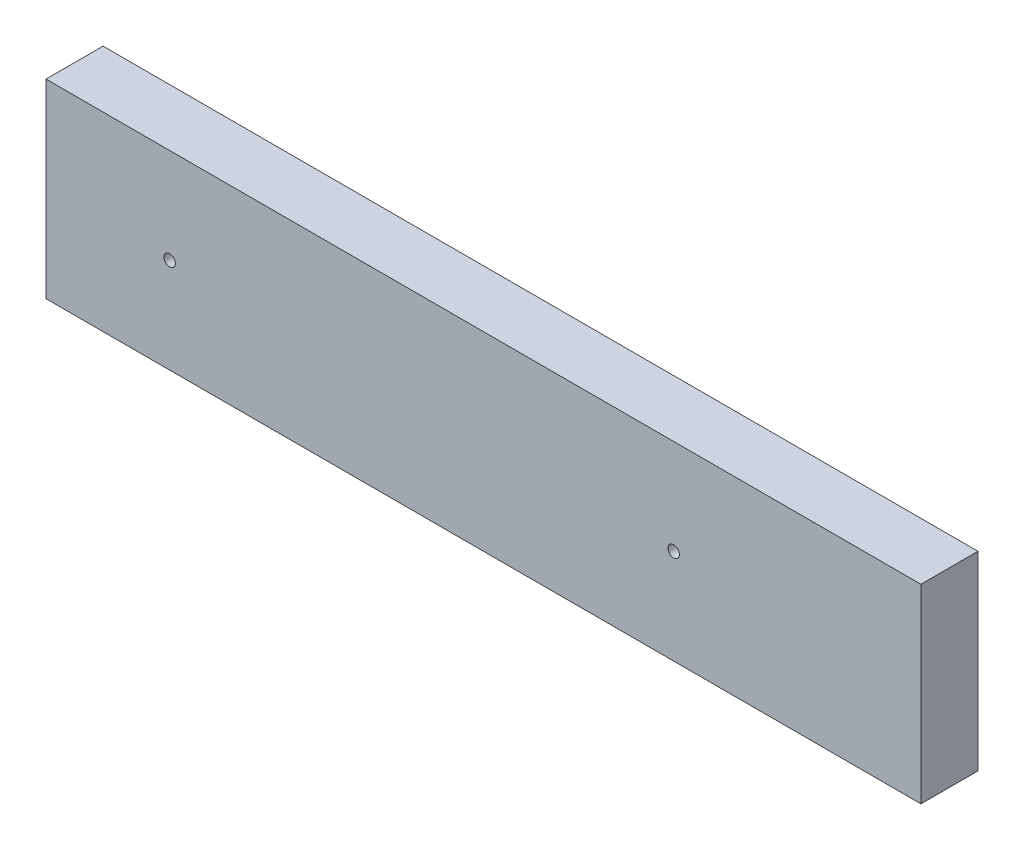
SolidWorks part; units mm, degrees
material "Pine"
ref_plane "Front Plane" through (0, 0, 0) normal (0, 0, 1) x (1, 0, 0)
ref_plane "Top Plane" through (0, 0, 0) normal (0, 1, 0) x (1, 0, 0)
ref_plane "Right Plane" through (0, 0, 0) normal (1, 0, 0) x (0, 0, -1)
sketch "Sketch1" plane through (0, 0, 0) normal (0, 0, 1) x (1, 0, 0)
  line L1 (-230, 50) -> (230, 50)
  line L2 (-230, 50) -> (-230, -50)
  line L3 (-230, -50) -> (230, -50)
  line L4 (230, 50) -> (230, -50)
  line L5 (-230, 50) -> (230, -50) construction
  line L6 (-230, -50) -> (230, 50) construction
  point P0 (0, 0)
  dimension "D1" = 100
  dimension "D2" = 460
extrude "Boss-Extrude1" add sketch "Sketch1" along normal blind 30
sketch "Sketch2" plane through (0, 0, 0) normal (0, 0, 1) x (1, 0, 0)
  circle A0 centre (100, 0) radius 3
  circle A1 centre (-165, 0) radius 3
  dimension "D1" = 6
  dimension "D2" = 100
  dimension "D3" = 165
extrude "Cut-Extrude1" cut sketch "Sketch2" along normal through all
